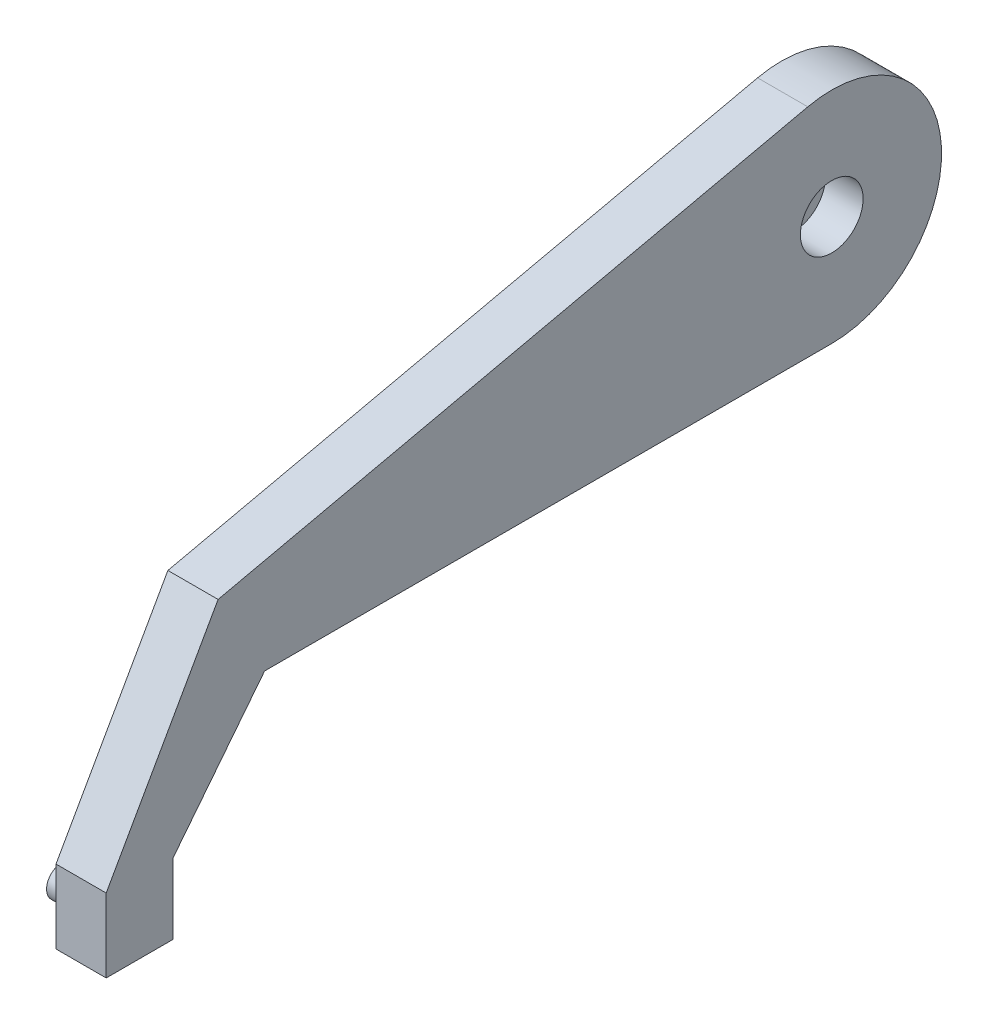
SolidWorks part; units mm, degrees
ref_plane "Front Plane" through (0, 0, 0) normal (0, 0, 1) x (1, 0, 0)
ref_plane "Top Plane" through (0, 0, 0) normal (0, 1, 0) x (1, 0, 0)
ref_plane "Right Plane" through (0, 0, 0) normal (1, 0, 0) x (0, 0, -1)
sketch "Sketch2" plane through (0, 0, 0) normal (1, 0, 0) x (0, 0, -1)
  line L7 (-880.2817, 714.2649) -> (-880.2817, 59.8876) construction
  line L8 (-2112.7113, 119.0847) -> (-1208.9162, 119.0847)
  line L9 (-2258.8353, -66.2762) -> (-2112.7113, 119.0847)
  line L10 (-2258.8353, -178.3756) -> (-2258.8353, -66.2762)
  line L11 (-2365.101, -178.3756) -> (-2258.8353, -178.3756)
  line L12 (-2365.101, -61.1263) -> (-2365.101, -178.3756)
  line L13 (-2186.804, 254.9131) -> (-2365.101, -61.1263)
  line L14 (-1247.0751, 464.8738) -> (-2186.804, 254.9131)
  arc A1 (-1247.0751, 464.8738) -> (-1208.9162, 119.0847) centre (-1208.9162, 294.0847) cw
extrude "Boss-Extrude1" add sketch "Sketch2" along normal blind 80
sketch "Sketch3" plane through (80, 0, 0) normal (1, 0, 0) x (0, 0, -1)
  circle A0 centre (-1208.9162, 294.0847) radius 50
  dimension "D1" = 100
extrude "Cut-Extrude1" cut sketch "Sketch3" against normal blind 60
sketch "Sketch4" plane through (0, 0, 0) normal (-1, 0, 0) x (0, 0, 1)
  line L0 (2365.101, -61.1263) -> (2365.101, -178.3756) construction
  line L1 (2365.101, -178.3756) -> (2258.8353, -178.3756) construction
  circle A0 centre (2305.101, -138.3756) radius 25
  dimension "D1" = 50
  dimension "D2" = 60
  dimension "D3" = 40
extrude "Boss-Extrude2" add sketch "Sketch4" along normal blind 50
